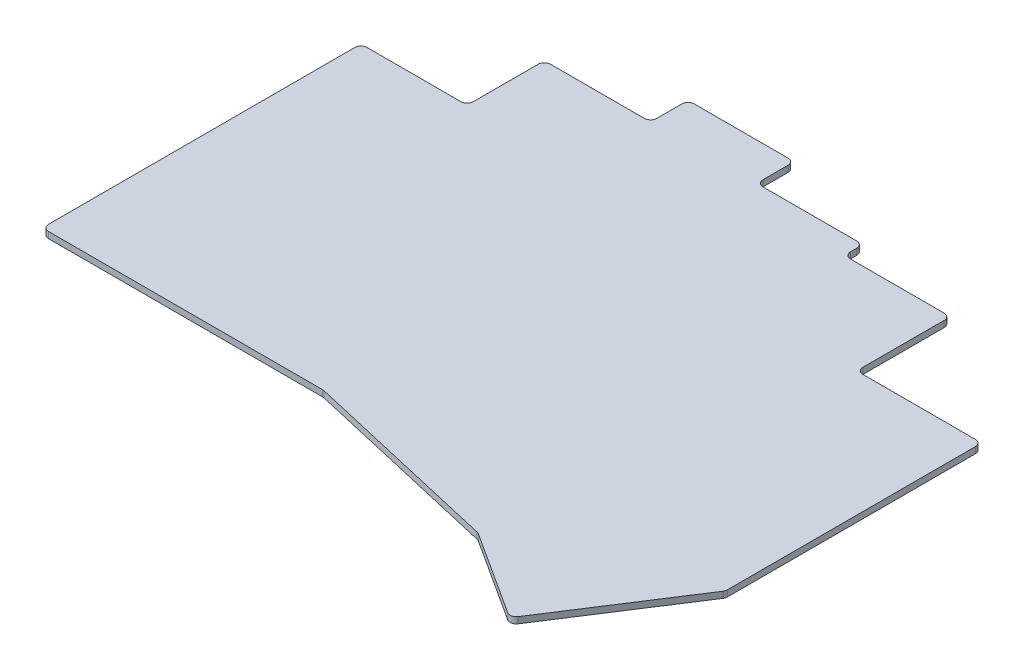
SolidWorks part; units mm, degrees
ref_plane "Plano frontal" through (0, 0, 0) normal (0, 0, 1) x (1, 0, 0)
ref_plane "Plano superior" through (0, 0, 0) normal (0, 1, 0) x (1, 0, 0)
ref_plane "Plano direito" through (0, 0, 0) normal (1, 0, 0) x (0, 0, -1)
sketch "Esboço1" plane through (0, 0, 0) normal (0, 1, 0) x (1, 0, 0)
  line L0 (-58.0334, 11.3261) -> (-58.0334, 62.3261)
  line L1 (-58.0334, 62.3261) -> (-41.0334, 62.3261)
  line L58 (-41.0334, 62.3261) -> (-41.0334, 74.6898)
  line L59 (-41.0334, 74.6898) -> (-24.0334, 74.6898)
  line L60 (-24.0334, 74.6898) -> (-24.0334, 80.6898)
  line L61 (-24.0334, 80.6898) -> (-7.0334, 80.6898)
  line L62 (-7.0334, 80.6898) -> (-7.0334, 74.6898)
  line L63 (-7.0334, 74.6898) -> (9.9666, 74.6898)
  line L64 (9.9666, 74.6898) -> (9.9666, 71.6898)
  line L65 (9.9666, 71.6898) -> (26.9666, 71.6898)
  line L66 (26.9666, 71.6898) -> (26.9666, 56.6898)
  line L67 (26.9666, 56.6898) -> (46.9666, 56.6898)
  line L68 (46.9666, 56.6898) -> (46.9666, 15.6898)
  line L69 (46.9666, 15.6898) -> (33.4036, -5.3113)
  line L70 (33.4036, -5.3113) -> (19.1229, 3.9116)
  line L71 (19.1229, 3.9116) -> (-13.0334, 11.3261)
  line L72 (-13.0334, 11.3261) -> (-58.0334, 11.3261)
  point P2 (46.8599, -11.6723)
  point P6 (46.9666, 30.7944)
  point P18 (0, 0)
  point P20 (37.1665, 0)
  point P21 (33.9293, -5.6416)
  dimension "D1" = 17
  dimension "D2" = 17
  dimension "D3" = 17
  dimension "D4" = 17
  dimension "D5" = 17
  dimension "D6" = 20
  dimension "D7" = 51
  dimension "D8" = 17
  dimension "D9" = 41
  dimension "D10" = 45
  dimension "D11" = 25
  dimension "D12" = 15
  dimension "D13" = 3
  dimension "D14" = 6
  dimension "D15" = 12.3636
  dimension "D16" = 33
extrude "Ressalto-extrusão1" add sketch "Esboço1" along normal blind 1
fillet "Filete1" radius 1 17 edges at (-7.0334, 0.5, -80.6898) (-7.0334, 0.5, -74.6898) (9.9666, 0.5, -74.6898) (9.9666, 0.5, -71.6898) (26.9666, 0.5, -71.6898) (26.9666, 0.5, -56.6898) (46.9666, 0.5, -56.6898) (46.9666, 0.5, -15.6898) (33.4036, 0.5, 5.3113) (19.1229, 0.5, -3.9116) (-13.0334, 0.5, -11.3261) (-58.0334, 0.5, -11.3261) (-58.0334, 0.5, -62.3261) (-41.0334, 0.5, -62.3261) (-41.0334, 0.5, -74.6898) (-24.0334, 0.5, -74.6898) (-24.0334, 0.5, -80.6898)
